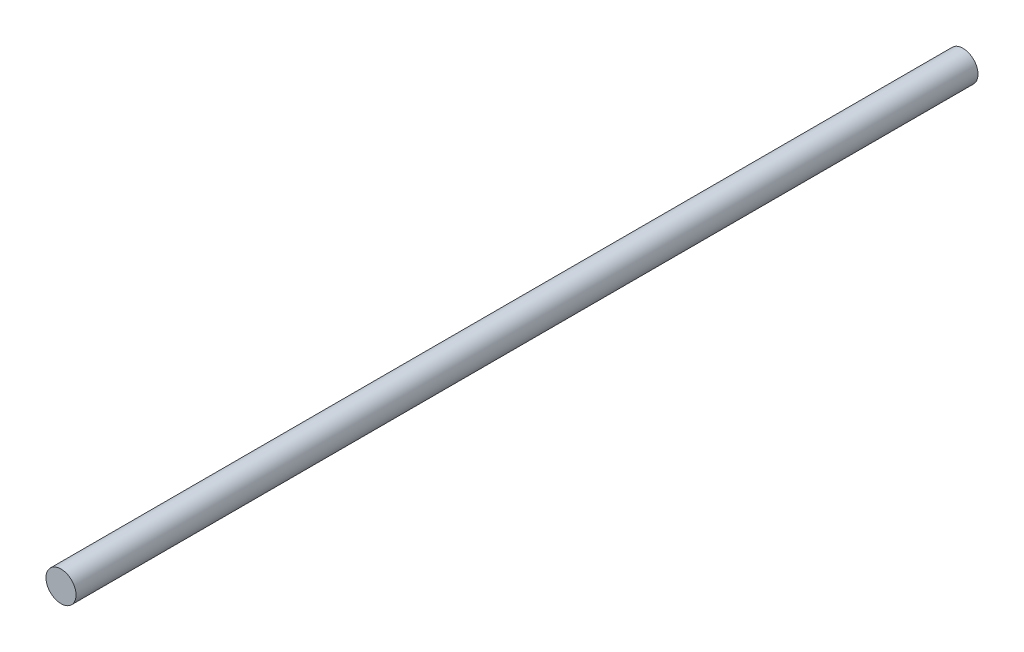
SolidWorks part; units mm, degrees
material "Простая углеродистая сталь"
ref_plane "Front" through (0, 0, 0) normal (0, 0, 1) x (1, 0, 0)
ref_plane "Top" through (0, 0, 0) normal (0, 1, 0) x (1, 0, 0)
ref_plane "Right" through (0, 0, 0) normal (1, 0, 0) x (0, 0, -1)
sketch "Эскиз1" plane through (0, 0, 0) normal (0, 0, 1) x (1, 0, 0)
  circle A0 centre (0, 0) radius 4
  dimension "D1" = 8
extrude "Бобышка-Вытянуть1" add sketch "Эскиз1" against normal mid plane 240
